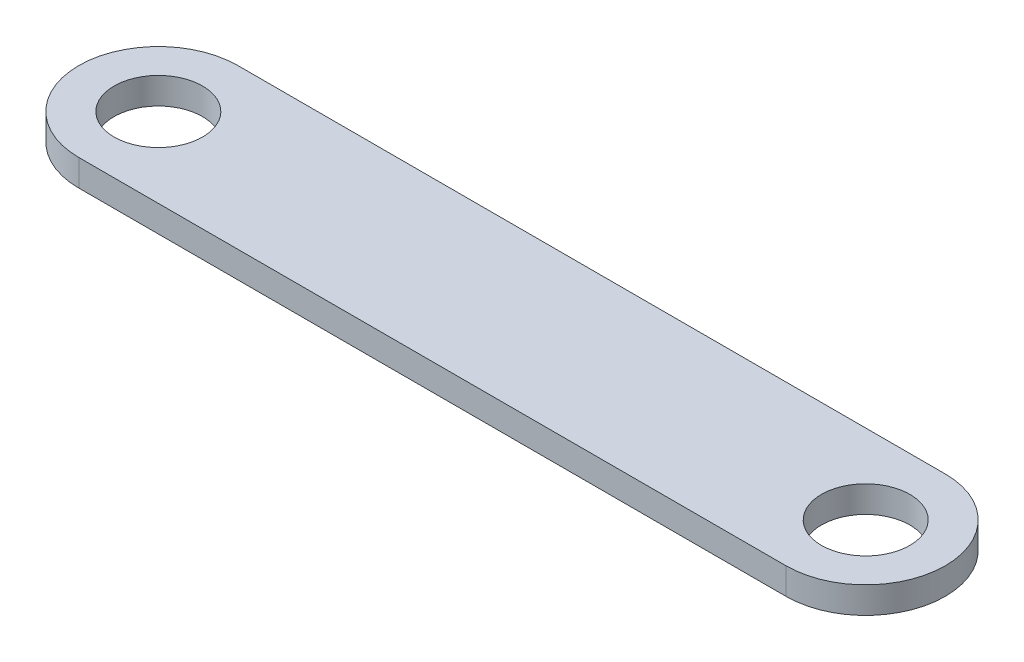
SolidWorks part; units mm, degrees
ref_plane "Front Plane" through (0, 0, 0) normal (0, 0, 1) x (1, 0, 0)
ref_plane "Top Plane" through (0, 0, 0) normal (0, 1, 0) x (1, 0, 0)
ref_plane "Right Plane" through (0, 0, 0) normal (1, 0, 0) x (0, 0, -1)
sketch "Sketch1" plane through (0, 0, 0) normal (0, 1, 0) x (1, 0, 0)
  line L0 (0, 0) -> (80, 0) construction
  line L1 (0, 9) -> (80, 9)
  line L2 (0, -9) -> (80, -9)
  arc A0 (0, 9) -> (0, -9) centre (0, 0) ccw
  arc A1 (80, -9) -> (80, 9) centre (80, 0) ccw
  circle A2 centre (0, 0) radius 5
  circle A3 centre (80, 0) radius 5
  point P3 (40, 0)
  dimension "D2" = 10
  dimension "D3" = 10
  dimension "D1" = 80
  dimension "D4" = 9
extrude "Boss-Extrude1" add sketch "Sketch1" along normal mid plane 3
